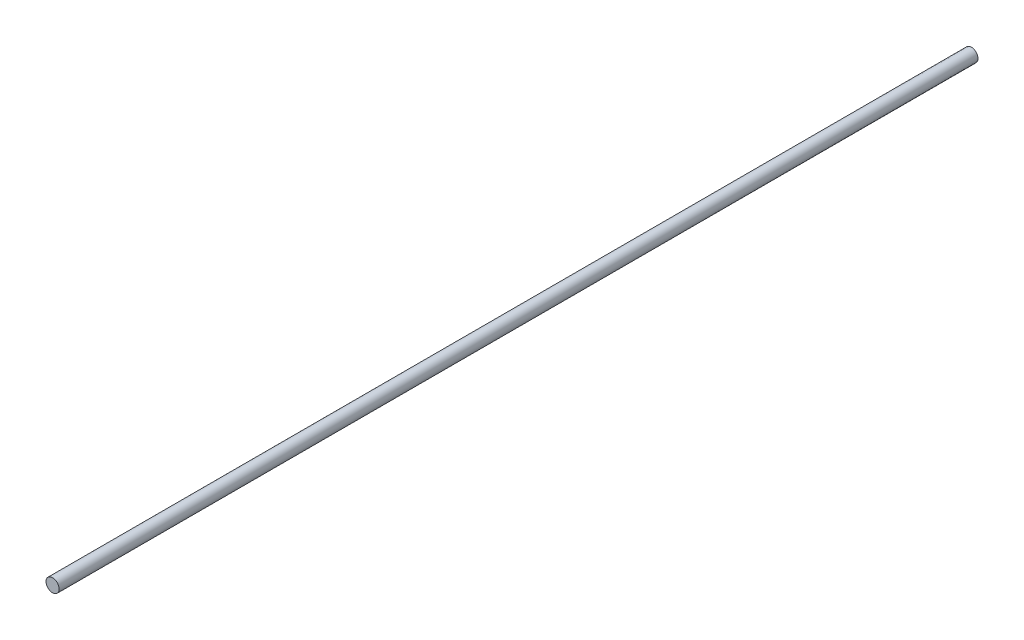
SolidWorks part; units mm, degrees
ref_plane "Front Plane" through (0, 0, 0) normal (0, 0, 1) x (1, 0, 0)
ref_plane "Top Plane" through (0, 0, 0) normal (0, 1, 0) x (1, 0, 0)
ref_plane "Right Plane" through (0, 0, 0) normal (1, 0, 0) x (0, 0, -1)
sketch "Sketch1" plane through (0, 0, 0) normal (0, 0, 1) x (1, 0, 0)
  circle A0 centre (0, 0) radius 2.5
  dimension "D1" = 5
extrude "Boss-Extrude1" add sketch "Sketch1" along normal mid plane 350
